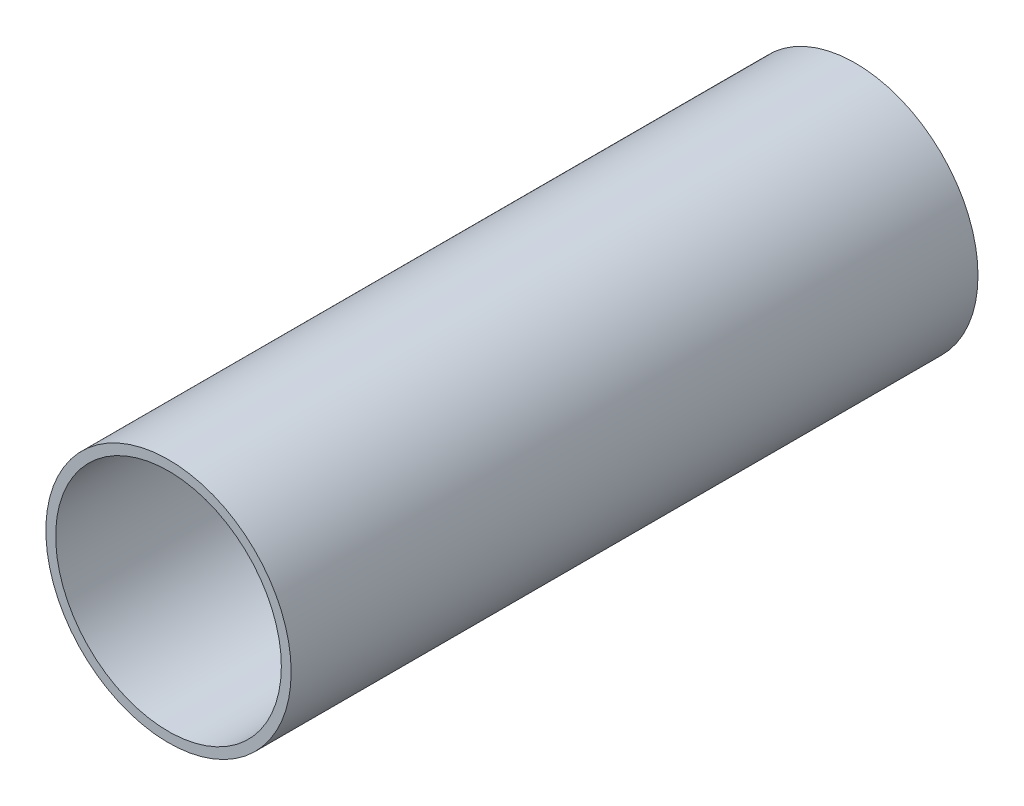
SolidWorks part; units mm, degrees
material "Thornel Mat VMA"
ref_plane "Front Plane" through (0, 0, 0) normal (0, 0, 1) x (1, 0, 0)
ref_plane "Top Plane" through (0, 0, 0) normal (0, 1, 0) x (1, 0, 0)
ref_plane "Right Plane" through (0, 0, 0) normal (1, 0, 0) x (0, 0, -1)
sketch "Sketch1" plane through (0, 0, 0) normal (0, 0, 1) x (1, 0, 0)
  circle A0 centre (0, 0) radius 25
  circle A1 centre (0, 0) radius 23
  dimension "D1" = 50
  dimension "D2" = 46
extrude "Boss-Extrude1" add sketch "Sketch1" along normal blind 40 and the other way blind 100
